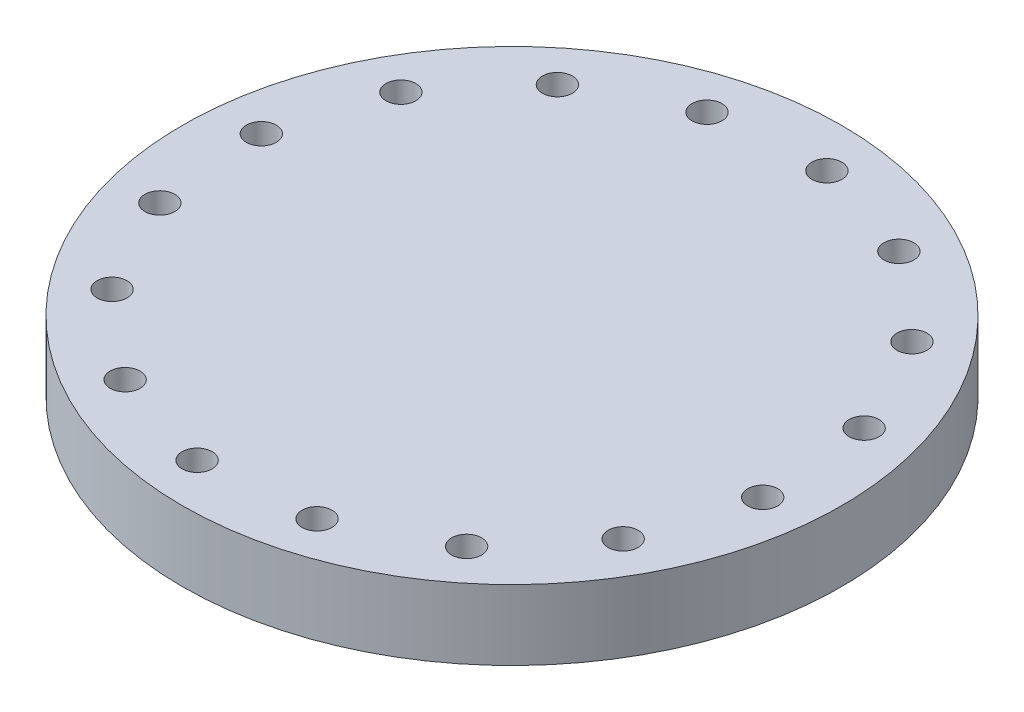
SolidWorks part; units mm, degrees
material "6061-T6 (SS)"
ref_plane "Front Plane" through (0, 0, 0) normal (0, 0, 1) x (1, 0, 0)
ref_plane "Top Plane" through (0, 0, 0) normal (0, 1, 0) x (1, 0, 0)
ref_plane "Right Plane" through (0, 0, 0) normal (1, 0, 0) x (0, 0, -1)
sketch "Sketch1" plane through (0, 0, 0) normal (0, 1, 0) x (1, 0, 0)
  circle A0 centre (0, 0) radius 27.5
  dimension "D1" = 55
extrude "Boss-Extrude1" add sketch "Sketch1" along normal mid plane 5.85
sketch "Sketch2" plane through (0, -2.925, 0) normal (0, -1, 0) x (1, 0, 0)
  arc A0 (22.0197, -5.6026) -> (23.6341, -7.5115) centre (22.8269, -6.557) ccw construction
  arc A1 (23.6341, -7.5115) -> (22.0197, -5.6026) centre (22.8269, -6.557) ccw construction
  arc A2 (22.7914, 3.632) -> (24.4058, 1.7231) centre (23.5986, 2.6776) ccw construction
  arc A3 (24.4058, 1.7231) -> (22.7914, 3.632) centre (23.5986, 2.6776) ccw construction
  arc A4 (17.7728, -13.839) -> (19.3873, -15.7478) centre (18.58, -14.7934) ccw construction
  arc A5 (19.3873, -15.7478) -> (17.7728, -13.839) centre (18.58, -14.7934) ccw construction
  arc A6 (10.6973, -19.8232) -> (12.3117, -21.732) centre (11.5045, -20.7776) ccw construction
  arc A7 (12.3117, -21.732) -> (10.6973, -19.8232) centre (11.5045, -20.7776) ccw construction
  arc A8 (1.8704, -22.6442) -> (3.4848, -24.553) centre (2.6776, -23.5986) ccw construction
  arc A9 (3.4848, -24.553) -> (1.8704, -22.6442) centre (2.6776, -23.5986) ccw construction
  arc A10 (-7.3642, -21.8725) -> (-5.7498, -23.7813) centre (-6.557, -22.8269) ccw construction
  arc A11 (-5.7498, -23.7813) -> (-7.3642, -21.8725) centre (-6.557, -22.8269) ccw construction
  arc A12 (-15.6006, -17.6256) -> (-13.9862, -19.5345) centre (-14.7934, -18.58) ccw construction
  arc A13 (-13.9862, -19.5345) -> (-15.6006, -17.6256) centre (-14.7934, -18.58) ccw construction
  arc A14 (-21.5848, -10.5501) -> (-19.9704, -12.459) centre (-20.7776, -11.5045) ccw construction
  arc A15 (-19.9704, -12.459) -> (-21.5848, -10.5501) centre (-20.7776, -11.5045) ccw construction
  arc A16 (-24.4058, -1.7231) -> (-22.7914, -3.632) centre (-23.5986, -2.6776) ccw construction
  arc A17 (-22.7914, -3.632) -> (-24.4058, -1.7231) centre (-23.5986, -2.6776) ccw construction
  arc A18 (-23.6341, 7.5115) -> (-22.0197, 5.6026) centre (-22.8269, 6.557) ccw construction
  arc A19 (-22.0197, 5.6026) -> (-23.6341, 7.5115) centre (-22.8269, 6.557) ccw construction
  arc A20 (-19.3873, 15.7478) -> (-17.7728, 13.839) centre (-18.58, 14.7934) ccw construction
  arc A21 (-17.7728, 13.839) -> (-19.3873, 15.7478) centre (-18.58, 14.7934) ccw construction
  arc A22 (-12.3117, 21.732) -> (-10.6973, 19.8232) centre (-11.5045, 20.7776) ccw construction
  arc A23 (-10.6973, 19.8232) -> (-12.3117, 21.732) centre (-11.5045, 20.7776) ccw construction
  arc A24 (-3.4848, 24.553) -> (-1.8704, 22.6442) centre (-2.6776, 23.5986) ccw construction
  arc A25 (-1.8704, 22.6442) -> (-3.4848, 24.553) centre (-2.6776, 23.5986) ccw construction
  arc A26 (5.7498, 23.7813) -> (7.3642, 21.8725) centre (6.557, 22.8269) ccw construction
  arc A27 (7.3642, 21.8725) -> (5.7498, 23.7813) centre (6.557, 22.8269) ccw construction
  arc A28 (19.9704, 12.459) -> (21.5848, 10.5501) centre (20.7776, 11.5045) ccw construction
  arc A29 (21.5848, 10.5501) -> (19.9704, 12.459) centre (20.7776, 11.5045) ccw construction
  arc A30 (13.9862, 19.5345) -> (15.6006, 17.6256) centre (14.7934, 18.58) ccw construction
  arc A31 (15.6006, 17.6256) -> (13.9862, 19.5345) centre (14.7934, 18.58) ccw construction
  arc A32 (22.0197, -5.6026) -> (23.6341, -7.5115) centre (22.8269, -6.557) ccw
  arc A33 (23.6341, -7.5115) -> (22.0197, -5.6026) centre (22.8269, -6.557) ccw
  arc A34 (22.7914, 3.632) -> (24.4058, 1.7231) centre (23.5986, 2.6776) ccw
  arc A35 (24.4058, 1.7231) -> (22.7914, 3.632) centre (23.5986, 2.6776) ccw
  arc A36 (17.7728, -13.839) -> (19.3873, -15.7478) centre (18.58, -14.7934) ccw
  arc A37 (19.3873, -15.7478) -> (17.7728, -13.839) centre (18.58, -14.7934) ccw
  arc A38 (10.6973, -19.8232) -> (12.3117, -21.732) centre (11.5045, -20.7776) ccw
  arc A39 (12.3117, -21.732) -> (10.6973, -19.8232) centre (11.5045, -20.7776) ccw
  arc A40 (1.8704, -22.6442) -> (3.4848, -24.553) centre (2.6776, -23.5986) ccw
  arc A41 (3.4848, -24.553) -> (1.8704, -22.6442) centre (2.6776, -23.5986) ccw
  arc A42 (-7.3642, -21.8725) -> (-5.7498, -23.7813) centre (-6.557, -22.8269) ccw
  arc A43 (-5.7498, -23.7813) -> (-7.3642, -21.8725) centre (-6.557, -22.8269) ccw
  arc A44 (-15.6006, -17.6256) -> (-13.9862, -19.5345) centre (-14.7934, -18.58) ccw
  arc A45 (-13.9862, -19.5345) -> (-15.6006, -17.6256) centre (-14.7934, -18.58) ccw
  arc A46 (-21.5848, -10.5501) -> (-19.9704, -12.459) centre (-20.7776, -11.5045) ccw
  arc A47 (-19.9704, -12.459) -> (-21.5848, -10.5501) centre (-20.7776, -11.5045) ccw
  arc A48 (-24.4058, -1.7231) -> (-22.7914, -3.632) centre (-23.5986, -2.6776) ccw
  arc A49 (-22.7914, -3.632) -> (-24.4058, -1.7231) centre (-23.5986, -2.6776) ccw
  arc A50 (-23.6341, 7.5115) -> (-22.0197, 5.6026) centre (-22.8269, 6.557) ccw
  arc A51 (-22.0197, 5.6026) -> (-23.6341, 7.5115) centre (-22.8269, 6.557) ccw
  arc A52 (-19.3873, 15.7478) -> (-17.7728, 13.839) centre (-18.58, 14.7934) ccw
  arc A53 (-17.7728, 13.839) -> (-19.3873, 15.7478) centre (-18.58, 14.7934) ccw
  arc A54 (-12.3117, 21.732) -> (-10.6973, 19.8232) centre (-11.5045, 20.7776) ccw
  arc A55 (-10.6973, 19.8232) -> (-12.3117, 21.732) centre (-11.5045, 20.7776) ccw
  arc A56 (-3.4848, 24.553) -> (-1.8704, 22.6442) centre (-2.6776, 23.5986) ccw
  arc A57 (-1.8704, 22.6442) -> (-3.4848, 24.553) centre (-2.6776, 23.5986) ccw
  arc A58 (5.7498, 23.7813) -> (7.3642, 21.8725) centre (6.557, 22.8269) ccw
  arc A59 (7.3642, 21.8725) -> (5.7498, 23.7813) centre (6.557, 22.8269) ccw
  arc A60 (19.9704, 12.459) -> (21.5848, 10.5501) centre (20.7776, 11.5045) ccw
  arc A61 (21.5848, 10.5501) -> (19.9704, 12.459) centre (20.7776, 11.5045) ccw
  arc A62 (13.9862, 19.5345) -> (15.6006, 17.6256) centre (14.7934, 18.58) ccw
  arc A63 (15.6006, 17.6256) -> (13.9862, 19.5345) centre (14.7934, 18.58) ccw
extrude "Cut-Extrude1" cut sketch "Sketch2" against normal through all
